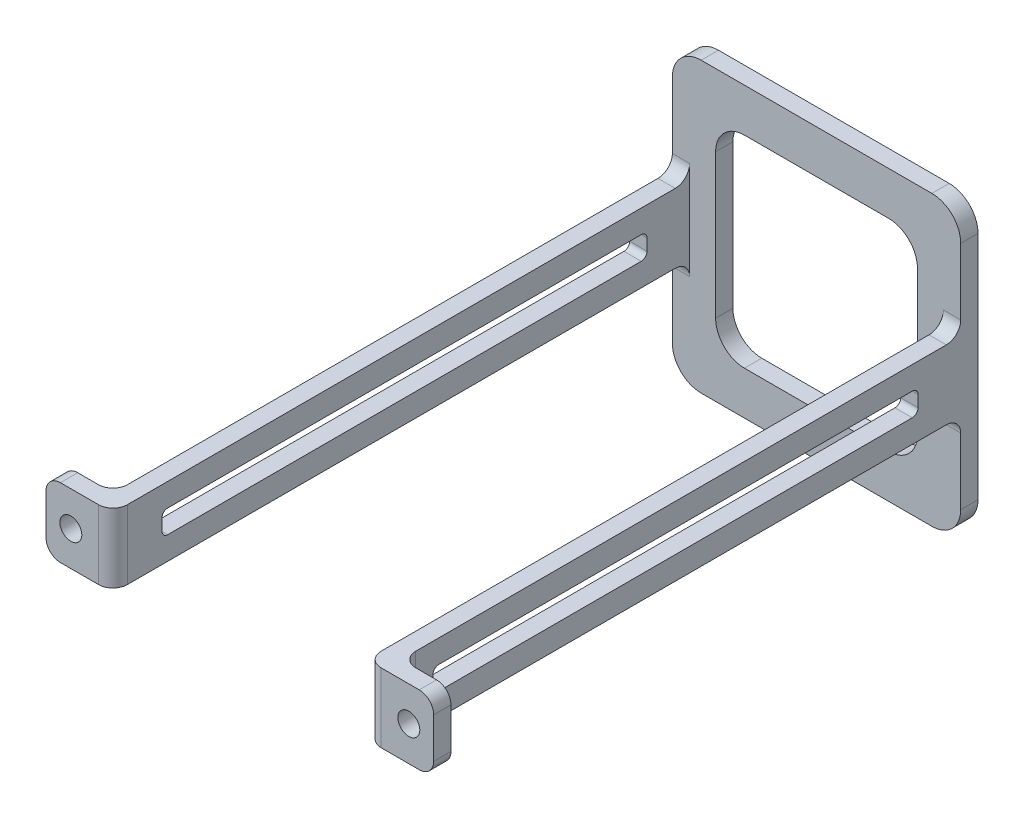
SolidWorks part; units mm, degrees
ref_plane "Front Plane" through (0, 0, 0) normal (0, 0, 1) x (1, 0, 0)
ref_plane "Top Plane" through (0, 0, 0) normal (0, 1, 0) x (1, 0, 0)
ref_plane "Right Plane" through (0, 0, 0) normal (1, 0, 0) x (0, 0, -1)
sketch "Sketch1" plane through (0, 0, 0) normal (0, 1, 0) x (1, 0, 0)
  line L0 (0, 0) -> (11.6105, 0)
  line L1 (11.6105, 0) -> (11.6105, 3)
  line L2 (11.6105, 3) -> (3, 3)
  line L3 (0, 0) -> (0, 100)
  line L4 (3, 100) -> (3, 3)
  line L5 (-44, 100) -> (0, 100)
  line L6 (-22, 100) -> (-22, 35.0645) construction
  line L7 (-47, 100) -> (-47, 3)
  line L8 (-44, 0) -> (-44, 100)
  line L9 (-55.6105, 3) -> (-47, 3)
  line L10 (-55.6105, 0) -> (-55.6105, 3)
  line L11 (-44, 0) -> (-55.6105, 0)
  line L12 (-47, 100) -> (-47, 103)
  line L13 (-47, 103) -> (3, 103)
  line L14 (3, 103) -> (3, 100)
extrude "Boss-Extrude1" add sketch "Sketch1" along normal mid plane 12
sketch "Sketch2" plane through (0, 0, 0) normal (0, 1, 0) x (1, 0, 0)
  line L1 (-47, 103) -> (3, 103)
  line L2 (-47, 103) -> (-47, 100)
  line L3 (-47, 100) -> (3, 100)
  line L4 (3, 103) -> (3, 100)
  line L12 (0, 100) -> (0, 0)
  line L13 (0, 0) -> (11.6105, 0)
  line L14 (11.6105, 0) -> (11.6105, 3)
  line L15 (11.6105, 3) -> (3, 3)
  line L16 (3, 3) -> (3, 103)
  line L17 (3, 103) -> (-47, 103)
  line L18 (-47, 103) -> (-47, 3)
  line L19 (-47, 3) -> (-55.6105, 3)
  line L20 (-55.6105, 3) -> (-55.6105, 0)
  line L21 (-55.6105, 0) -> (-44, 0)
  line L22 (-44, 0) -> (-44, 100)
  line L23 (-44, 100) -> (0, 100)
  line L25 (0, 0) -> (11.6105, 0)
  line L26 (11.6105, 0) -> (11.6105, 3)
  line L27 (11.6105, 3) -> (3, 3)
  line L28 (3, 100) -> (3, 103)
  line L29 (3, 103) -> (-47, 103)
  line L30 (-47, 103) -> (-47, 100)
  line L31 (-47, 3) -> (-55.6105, 3)
  line L32 (-55.6105, 3) -> (-55.6105, 0)
  line L33 (-55.6105, 0) -> (-44, 0)
  line L35 (-44, 100) -> (0, 100)
  dimension "D1" = 0
extrude "Boss-Extrude2" add sketch "Sketch2" along normal mid plane 50 contours L4 L1 L2 L3
ref_plane "Plane2" through (-55.6105, -6, -3) normal (0, 0, 1) x (1, 0, 0)
sketch "Sketch4" plane through (0, 0, -3) normal (0, 0, -1) x (-1, 0, 0)
  line L0 (47, 6) -> (55.6105, -6) construction
  line L4 (47, -6) -> (55.6105, -6)
  line L5 (55.6105, -6) -> (55.6105, 6)
  line L6 (55.6105, 6) -> (47, 6)
  line L7 (47, 6) -> (47, -6)
  line L8 (47, -6) -> (55.6105, -6)
  line L9 (55.6105, -6) -> (55.6105, 6)
  line L10 (55.6105, 6) -> (47, 6)
  line L11 (47, 6) -> (47, -6)
  circle A0 centre (51.3052, 0) radius 1.9
  point P4 (0, 0)
  dimension "D1" = 0
extrude "Cut-Extrude1" cut sketch "Sketch4" against normal blind 50 contours A0 L0 | L0 A0
ref_plane "Plane3" through (-22, 0, 0) normal (1, 0, 0) x (0, 0, -1)
mirror "Mirror1" about plane through (-22, 0, 0) normal (1, 0, 0) of "Cut-Extrude1"
sketch "Sketch5" plane through (0, 0, -3) normal (0, 0, -1) x (-1, 0, 0)
  circle A0 centre (51.3052, 0) radius 4
sketch "Sketch6" plane through (0, 0, -103) normal (0, 0, -1) x (-1, 0, 0)
  line L0 (-3, -6) -> (-3, -25) construction
  line L1 (9.5, -17.5) -> (34.5, -17.5)
  line L2 (4.5, -12.5) -> (4.5, 12.5)
  line L3 (9.5, 17.5) -> (34.5, 17.5)
  line L4 (39.5, -12.5) -> (39.5, 12.5)
  line L5 (47, -25) -> (-3, -25) construction
  line L6 (47, 25) -> (47, 6) construction
  line L7 (47, 25) -> (-3, 25) construction
  arc A0 (4.5, 12.5) -> (9.5, 17.5) centre (9.5, 12.5) cw
  arc A1 (34.5, 17.5) -> (39.5, 12.5) centre (34.5, 12.5) cw
  arc A2 (34.5, -17.5) -> (39.5, -12.5) centre (34.5, -12.5) ccw
  arc A3 (9.5, -17.5) -> (4.5, -12.5) centre (9.5, -12.5) cw
  dimension "D5" = 5
  dimension "D1" = 7.5
  dimension "D2" = 7.5
  dimension "D3" = 7.5
  dimension "D4" = 7.5
extrude "Cut-Extrude2" cut sketch "Sketch6" against normal mid plane 50 contours A3 L1 A2 L4 A1 L3 A0 L2
fillet "Fillet1" radius 5 4 edges at (3, 25, -101.5) (3, -25, -101.5) (-47, 25, -101.5) (-47, -25, -101.5)
fillet "Fillet2" radius 2.5 12 edges at (11.6105, -6, -1.5) (11.6105, 6, -1.5) (-55.6105, -6, -1.5) (-55.6105, 6, -1.5) (-47, 0, -3) (-44, 0, 0) (0, 0, 0) (3, 0, -3) (-45.5, 6, -100) (-45.5, -6, -100) (1.5, -6, -100) (1.5, 6, -100)
sketch "Sketch7" plane through (-47, 0, 0) normal (-1, 0, 0) x (0, 0, 1)
  line L0 (-97.5, 6) -> (-5.5, 6) construction
  line L1 (-91.6045, 2) -> (-9.5, 2)
  line L2 (-92.6045, 1) -> (-92.6045, -1)
  line L3 (-91.6045, -2) -> (-9.5, -2)
  line L4 (-8.5, 1) -> (-8.5, -1)
  line L5 (-97.5, -6) -> (-5.5, -6) construction
  line L6 (-5.5, 0.5926) -> (-5.5, 6) construction
  arc A0 (-9.5, -2) -> (-8.5, -1) centre (-9.5, -1) ccw
  arc A1 (-9.5, 2) -> (-8.5, 1) centre (-9.5, 1) cw
  arc A2 (-92.6045, -1) -> (-91.6045, -2) centre (-91.6045, -1) ccw
  arc A3 (-91.6045, 2) -> (-92.6045, 1) centre (-91.6045, 1) ccw
  dimension "D4" = 1
  dimension "D1" = 4
  dimension "D2" = 4
  dimension "D3" = 3
extrude "Cut-Extrude3" cut sketch "Sketch7" against normal blind 88
